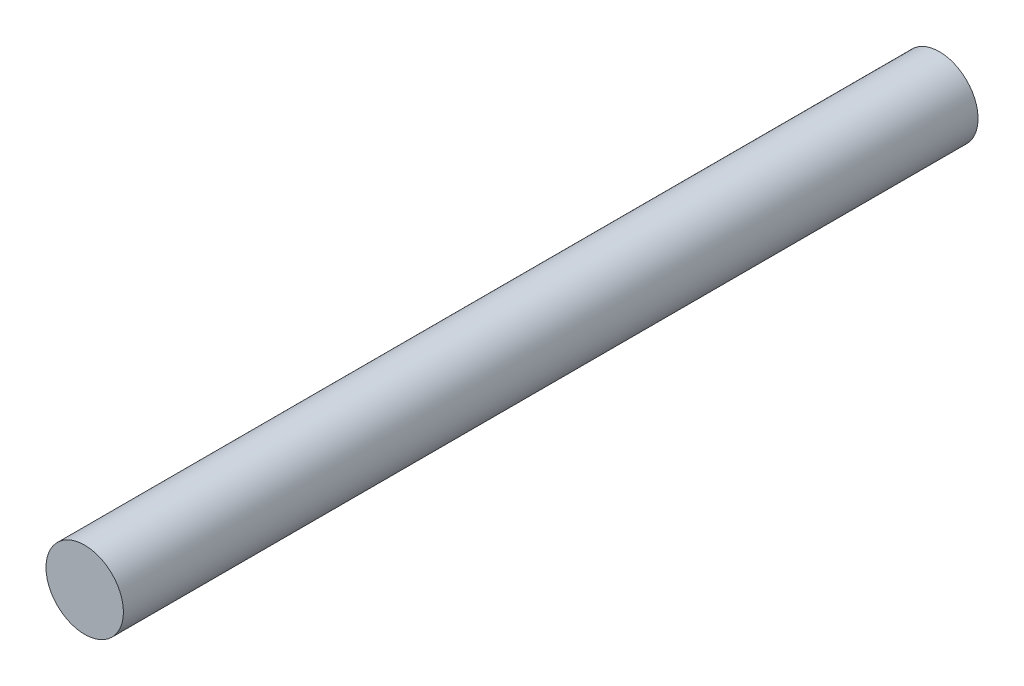
SolidWorks part; units mm, degrees
ref_plane "Спереди" through (0, 0, 0) normal (0, 0, 1) x (1, 0, 0)
ref_plane "Сверху" through (0, 0, 0) normal (0, 1, 0) x (1, 0, 0)
ref_plane "Справа" through (0, 0, 0) normal (1, 0, 0) x (0, 0, -1)
sketch "Эскиз1" plane through (0, 0, 0) normal (0, 0, 1) x (1, 0, 0)
  circle A0 centre (0, 0) radius 5.25
  dimension "D1" = 10.5
extrude "Вытянуть1" add sketch "Эскиз1" along normal blind 116
